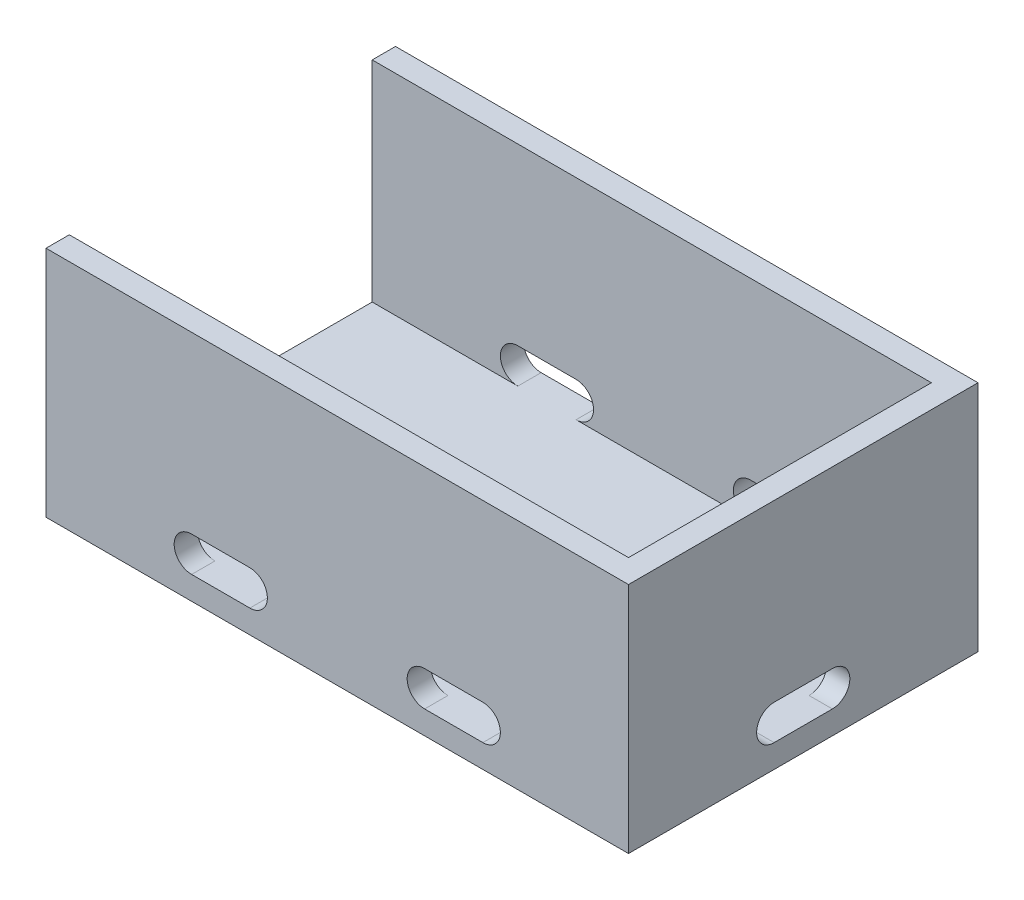
SolidWorks part; units mm, degrees
material "ABS"
ref_plane "Front Plane" through (0, 0, 0) normal (0, 0, 1) x (1, 0, 0)
ref_plane "Top Plane" through (0, 0, 0) normal (0, 1, 0) x (1, 0, 0)
ref_plane "Right Plane" through (0, 0, 0) normal (1, 0, 0) x (0, 0, -1)
sketch "Sketch1" plane through (0, 0, 0) normal (0, 1, 0) x (1, 0, 0)
  line L0 (0, 15) -> (71.3343, 15) construction
  line L1 (0, 0) -> (50, 0)
  line L2 (0, 0) -> (0, 2)
  line L3 (0, 30) -> (50, 30)
  line L4 (50, 0) -> (50, 30)
  line L5 (0, 30) -> (50, 30)
  line L6 (0, 30) -> (0, 28)
  line L7 (0, 28) -> (48, 28)
  line L8 (50, 30) -> (50, 28)
  line L9 (50, 0) -> (50, 2)
  line L10 (0, 2) -> (48, 2)
  line L11 (0, 0) -> (0, 2)
  line L12 (0, 0) -> (50, 0)
  line L13 (0, 0) -> (50, 0)
  line L14 (0, 28) -> (0, 30)
  line L16 (48, 28) -> (48, 2)
  line L18 (50, 28) -> (50, 2)
  dimension "D1" = 50
  dimension "D2" = 30
  dimension "D3" = 2
  dimension "D4" = 2
extrude "Extrude-Thin1" add sketch "Sketch1" along normal blind 18 thin contours L7 L16 L10
sketch "Sketch2" plane through (0, 0, 0) normal (0, -1, 0) x (1, 0, 0)
  line L1 (0, 0) -> (50, 0)
  line L2 (0, 0) -> (0, -30)
  line L3 (0, -30) -> (50, -30)
  line L4 (50, 0) -> (50, -30)
extrude "Boss-Extrude1" add sketch "Sketch2" along normal blind 2
sketch "Sketch3" plane through (0, 0, 0) normal (0, 0, 1) x (1, 0, 0)
  line L0 (0, 18) -> (0, -2) construction
  line L1 (50, -2) -> (0, -2)
  line L2 (50, -2) -> (50, 0)
  line L3 (50, 0) -> (0, 0)
  line L4 (0, -2) -> (0, 0)
  line L5 (12.5, 1.5) -> (17.5, 1.5) construction
  line L6 (12.5, 3) -> (17.5, 3)
  line L7 (12.5, 0) -> (17.5, 0)
  line L8 (25, 18) -> (25, -5.8681) construction
  line L9 (50, 18) -> (0, 18) construction
  line L10 (37.5, 1.5) -> (32.5, 1.5) construction
  line L11 (37.5, 3) -> (32.5, 3)
  line L12 (37.5, 0) -> (32.5, 0)
  arc A0 (12.5, 3) -> (12.5, 0) centre (12.5, 1.5) ccw
  arc A1 (17.5, 0) -> (17.5, 3) centre (17.5, 1.5) ccw
  arc A2 (37.5, 3) -> (37.5, 0) centre (37.5, 1.5) cw
  arc A3 (32.5, 0) -> (32.5, 3) centre (32.5, 1.5) cw
  point P9 (15, 1.5)
  point P20 (35, 1.5)
  dimension "D2" = 1.5
  dimension "D1" = 2
  dimension "D3" = 5
  dimension "D4" = 1.5
  dimension "D5" = 12.5
extrude "Cut-Extrude1" cut sketch "Sketch3" against normal through all both and the other way through all contours L7 A1 L6 A0 | L11 A3 L12 A2
sketch "Sketch4" plane through (48, 0, 0) normal (-1, 0, 0) x (0, 0, 1)
  line L0 (-17.5, 1.5) -> (-12.5, 1.5) construction
  line L1 (-17.5, 3) -> (-12.5, 3)
  line L2 (-17.5, 0) -> (-12.5, 0)
  line L3 (-28, 18) -> (-28, 0) construction
  line L4 (-28, 0) -> (-2, 0) construction
  arc A0 (-17.5, 3) -> (-17.5, 0) centre (-17.5, 1.5) ccw
  arc A1 (-12.5, 0) -> (-12.5, 3) centre (-12.5, 1.5) ccw
  point P2 (-15, 1.5)
  dimension "D1" = 1.5
  dimension "D2" = 5
  dimension "D3" = 13
  dimension "D4" = 1.5
extrude "Cut-Extrude2" cut sketch "Sketch4" against normal through all both and the other way through all
